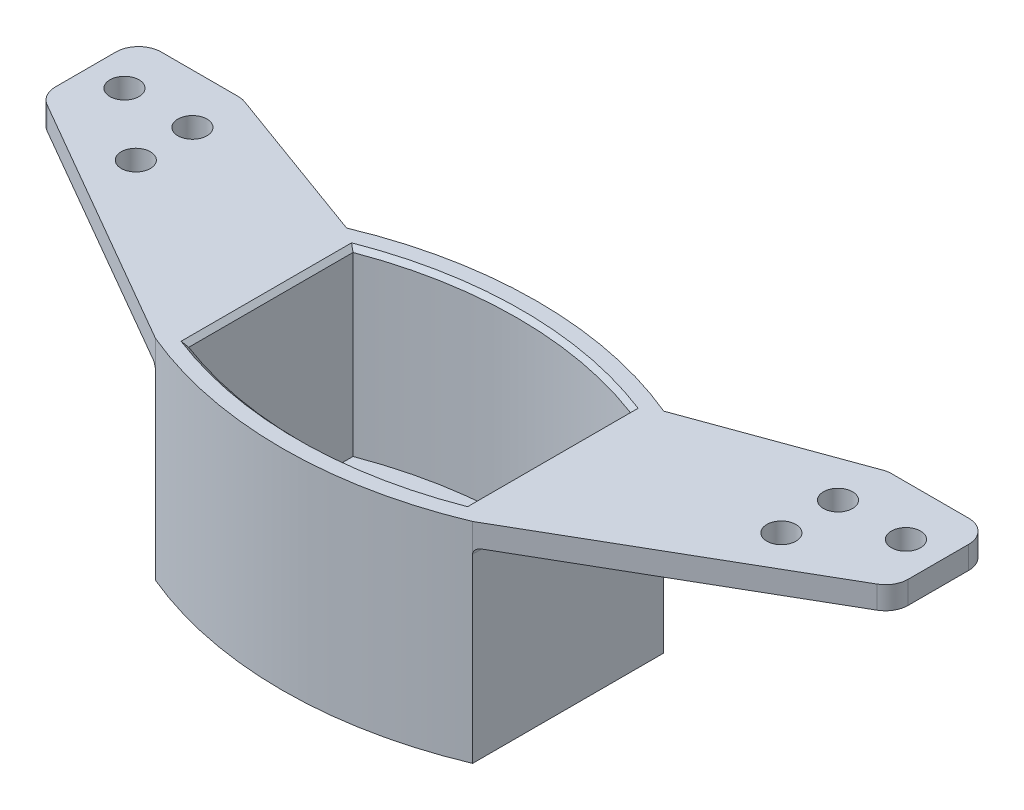
SolidWorks part; units mm, degrees
ref_plane "Front Plane" through (0, 0, 0) normal (0, 0, 1) x (1, 0, 0)
ref_plane "Top Plane" through (0, 0, 0) normal (0, 1, 0) x (1, 0, 0)
ref_plane "Right Plane" through (0, 0, 0) normal (1, 0, 0) x (0, 0, -1)
sketch "Sketch1" plane through (0, 0, 0) normal (0, 1, 0) x (1, 0, 0)
  line L0 (0, 11.43) -> (0, -11.43) construction
  line L1 (-35.56, 21.4311) -> (-35.56, -21.4311)
  line L3 (35.56, 21.4311) -> (35.56, -21.4311)
  circle A0 centre (-22.86, 11.43) radius 3.675
  circle A1 centre (0, 11.43) radius 3.675
  circle A2 centre (22.86, 11.43) radius 3.675
  circle A3 centre (0, -11.43) radius 3.675
  arc A4 (35.56, 21.4311) -> (-35.56, 21.4311) centre (0, -63.5) ccw
  arc A5 (-35.56, -21.4311) -> (35.56, -21.4311) centre (0, 63.5) ccw
  point P0 (0, 0)
  point P1 (0, 0)
  dimension "D1" = 7.35
  dimension "D5" = 184.15
  dimension "D2" = 22.86
  dimension "D3" = 22.86
  dimension "D4" = 22.86
  dimension "D6" = 63.5
  dimension "D7" = 63.5
  dimension "D8" = 35.56
  dimension "D9" = 35.56
extrude "Boss-Extrude1" add sketch "Sketch1" against normal blind 6.35
sketch "Sketch2" plane through (0, 0, 0) normal (0, 1, 0) x (1, 0, 0)
  line L0 (-31.115, 18.4199) -> (-31.115, -18.4199)
  line L1 (31.115, -18.4199) -> (31.115, 18.4199)
  line L2 (-35.56, 21.4311) -> (-35.56, -21.4311)
  line L3 (35.56, -21.4311) -> (35.56, 21.4311)
  line L4 (-35.56, 21.4311) -> (-35.56, -21.4311)
  line L5 (35.56, -21.4311) -> (35.56, 21.4311)
  arc A0 (31.115, 18.4199) -> (-31.115, 18.4199) centre (0, -63.5) ccw
  arc A1 (-31.115, -18.4199) -> (31.115, -18.4199) centre (0, 63.5) ccw
  arc A2 (35.56, 21.4311) -> (-35.56, 21.4311) centre (0, -63.5) ccw
  arc A3 (-35.56, -21.4311) -> (35.56, -21.4311) centre (0, 63.5) ccw
  arc A4 (35.56, 21.4311) -> (-35.56, 21.4311) centre (0, -63.5) ccw
  arc A5 (-35.56, -21.4311) -> (35.56, -21.4311) centre (0, 63.5) ccw
  dimension "D1" = 0
  dimension "D2" = 4.445
extrude "Boss-Extrude2" add sketch "Sketch2" along normal blind 40.64
chamfer "Chamfer1" distance 1.016 angle 45 4 edges at (31.115, 40.64, 0) (0, 40.64, 24.13) (-31.115, 40.64, 0) (0, 40.64, -24.13)
sketch "Sketch3" plane through (0, 40.64, 0) normal (0, 1, 0) x (1, 0, 0)
  line L0 (-35.56, -21.4311) -> (-95.6227, 13.2461)
  line L1 (-95.6227, 13.2461) -> (-95.6227, 34.8361)
  line L2 (-95.6227, 34.8361) -> (-72.39, 34.8361)
  line L3 (-72.39, 34.8361) -> (-35.56, 21.4311)
  line L4 (-35.56, 21.4311) -> (-35.56, -21.4311) construction
  line L5 (-35.56, 21.4311) -> (-35.56, -21.4311)
  line L6 (-72.39, 34.8361) -> (-72.39, -0.1673) construction
  line L7 (-72.39, 23.6844) -> (-72.39, 10.9844) construction
  circle A0 centre (-87.63, 23.6844) radius 3.2639
  circle A1 centre (-72.39, 23.6844) radius 3.2639
  circle A2 centre (-72.39, 10.9844) radius 3.2639
  point P14 (-72.39, 17.3344)
  point P15 (-72.39, 17.3344)
  dimension "D1" = 6.5278
  dimension "D2" = 15.24
  dimension "D3" = 12.7
  dimension "D4" = 21.59
  dimension "D6" = 60
  dimension "D7" = 70
  dimension "D8" = 36.83
extrude "Boss-Extrude3" add sketch "Sketch3" against normal blind 5.08
fillet "Fillet1" radius 5.08 3 edges at (-72.39, 38.1, -34.8361) (-95.6227, 38.1, -13.2461) (-95.6227, 38.1, -34.8361)
mirror "Mirror1" about plane through (0, 0, 0) normal (1, 0, 0) of "Fillet1", "Boss-Extrude3"
fillet "Fillet2" radius 1.27 2 edges at (35.56, 35.56, 0) (-35.56, 35.56, 0)
